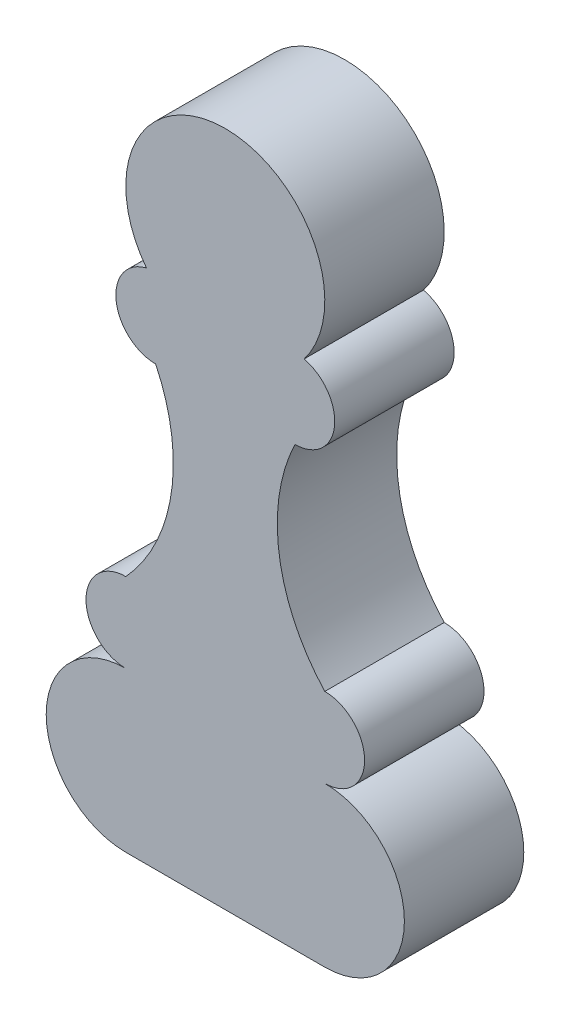
SolidWorks part; units mm, degrees
ref_plane "Front Plane" through (0, 0, 0) normal (0, 0, 1) x (1, 0, 0)
ref_plane "Top Plane" through (0, 0, 0) normal (0, 1, 0) x (1, 0, 0)
ref_plane "Right Plane" through (0, 0, 0) normal (1, 0, 0) x (0, 0, -1)
sketch "Sketch1" plane through (0, 0, 0) normal (0, 0, 1) x (1, 0, 0)
  line L0 (0, 25) -> (0, -135)
  line L1 (-17.5, -25) -> (17.5, -25) construction
  line L2 (-17.5, -15) -> (17.5, -15)
  line L3 (-17.5, -35) -> (17.5, -35)
  line L4 (-25, -95) -> (25, -95) construction
  line L5 (-25, -85) -> (25, -85)
  line L6 (-25, -105) -> (25, -105)
  line L7 (-25, -125) -> (25, -125) construction
  line L8 (-25, -105) -> (25, -105)
  line L9 (-25, -145) -> (25, -145)
  circle A0 centre (0, 0) radius 25
  arc A1 (-17.5, -15) -> (-17.5, -35) centre (-17.5, -25) ccw
  arc A2 (17.5, -35) -> (17.5, -15) centre (17.5, -25) ccw
  arc A3 (-25, -85) -> (-25, -105) centre (-25, -95) ccw
  arc A4 (25, -105) -> (25, -85) centre (25, -95) ccw
  arc A5 (-25, -105) -> (-25, -145) centre (-25, -125) ccw
  arc A6 (25, -145) -> (25, -105) centre (25, -125) ccw
  arc A7 (-17.5, -35) -> (-25, -85) centre (-58.0663, -54.4776) cw
  arc A8 (17.5, -35) -> (25, -85) centre (58.0663, -54.4776) ccw
  point P7 (0, -25)
  point P14 (0, -95)
  point P20 (0, -125)
  point P26 (-25, -124.2821)
  point P33 (25, -126.0672)
  dimension "D1" = 50
  dimension "D2" = 160
  dimension "D4" = 10
  dimension "D6" = 10
  dimension "D8" = 45
  dimension "D9" = 45
  dimension "D10" = 20
  dimension "D3" = 35
  dimension "D5" = 70
  dimension "D7" = 50
  dimension "D11" = 50
extrude "Boss-Extrude3" add sketch "Sketch1" along normal blind 30
